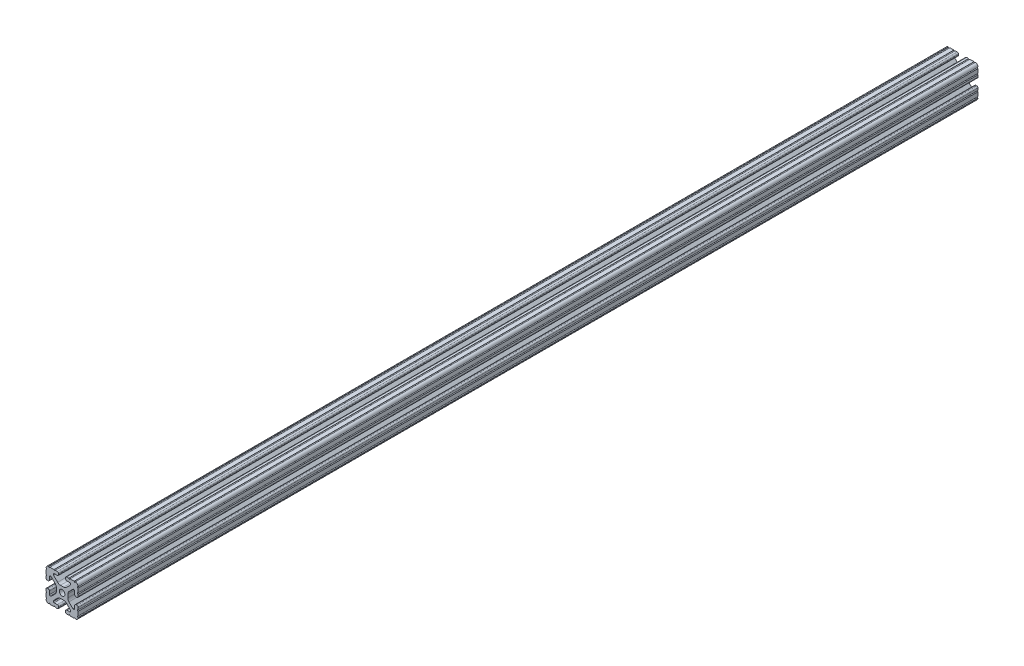
SolidWorks part; units mm, degrees
material "6061 Alloy"
ref_plane "Front Plane" through (0, 0, 0) normal (0, 0, 1) x (1, 0, 0)
ref_plane "Top Plane" through (0, 0, 0) normal (0, 1, 0) x (1, 0, 0)
ref_plane "Right Plane" through (0, 0, 0) normal (1, 0, 0) x (0, 0, -1)
sketch "Sketch1" plane through (0, 0, 0) normal (0, 0, 1) x (1, 0, 0)
  line L0 (0, 25.6181) -> (0, -24.623) construction
  line L1 (-20.8943, 0) -> (20.4607, 0) construction
  line L2 (-10.0229, 12.9148) -> (-5.2522, 8.144)
  line L3 (-10.287, 14.0843) -> (-10.287, 13.5524)
  line L4 (-5.6176, 14.986) -> (-9.3853, 14.986)
  line L5 (-4.064, 17.4964) -> (-4.064, 16.5396)
  line L6 (-7.9742, 19.05) -> (-5.6176, 19.05)
  line L7 (-14.3277, 19.05) -> (-9.4982, 19.05)
  line L8 (-19.05, 9.4961) -> (-19.05, 14.3277)
  line L9 (-19.05, 5.6176) -> (-19.05, 7.9763)
  line L10 (-16.5396, 4.064) -> (-17.4964, 4.064)
  line L11 (-14.986, 9.3853) -> (-14.986, 5.6176)
  line L12 (-13.516, 10.287) -> (-14.0843, 10.287)
  line L13 (-8.1476, 5.2921) -> (-12.8784, 10.0229)
  line L14 (-6.7564, -1.9335) -> (-6.7564, 1.9335)
  line L15 (-12.8784, -10.0229) -> (-8.1476, -5.2921)
  line L16 (-14.0843, -10.287) -> (-13.516, -10.287)
  line L17 (-14.986, -5.6176) -> (-14.986, -9.3853)
  line L18 (-17.4964, -4.064) -> (-16.5396, -4.064)
  line L19 (-19.05, -7.9763) -> (-19.05, -5.6176)
  line L20 (-19.05, -14.3277) -> (-19.05, -9.4961)
  line L21 (-9.4961, -19.05) -> (-14.3277, -19.05)
  line L22 (-5.6176, -19.05) -> (-7.9763, -19.05)
  line L23 (-4.064, -17.4964) -> (-4.064, -16.5396)
  line L24 (10.0229, -12.9148) -> (5.2522, -8.144)
  line L25 (10.287, -14.0843) -> (10.287, -13.5524)
  line L26 (5.6176, -14.986) -> (9.3853, -14.986)
  line L28 (-1.9022, 6.7564) -> (1.9022, 6.7564)
  line L29 (-1.9022, -6.7564) -> (1.9022, -6.7564)
  line L31 (-5.6176, -14.986) -> (-9.3853, -14.986)
  line L32 (-10.287, -14.0843) -> (-10.287, -13.5524)
  line L33 (-10.0229, -12.9148) -> (-5.2522, -8.144)
  line L66 (4.064, -16.5396) -> (4.064, -17.4964)
  line L67 (5.6176, -19.05) -> (7.9763, -19.05)
  line L68 (9.4961, -19.05) -> (14.3277, -19.05)
  line L69 (19.05, -14.3277) -> (19.05, -9.4961)
  line L70 (19.05, -7.9763) -> (19.05, -5.6176)
  line L71 (17.4964, -4.064) -> (16.5396, -4.064)
  line L72 (14.986, -5.6176) -> (14.986, -9.3853)
  line L73 (14.0843, -10.287) -> (13.516, -10.287)
  line L74 (12.8784, -10.0229) -> (8.1476, -5.2921)
  line L75 (6.7564, -1.9335) -> (6.7564, 1.9335)
  line L76 (8.1476, 5.2921) -> (12.8784, 10.0229)
  line L77 (13.516, 10.287) -> (14.0843, 10.287)
  line L78 (14.986, 9.3853) -> (14.986, 5.6176)
  line L79 (16.5396, 4.064) -> (17.4964, 4.064)
  line L80 (19.05, 5.6176) -> (19.05, 7.9763)
  line L81 (19.05, 9.4961) -> (19.05, 14.3277)
  line L82 (14.3277, 19.05) -> (9.4982, 19.05)
  line L83 (7.9742, 19.05) -> (5.6176, 19.05)
  line L84 (4.064, 17.4964) -> (4.064, 16.5396)
  line L85 (5.6176, 14.986) -> (9.3853, 14.986)
  line L86 (10.287, 14.0843) -> (10.287, 13.5524)
  line L87 (10.0229, 12.9148) -> (5.2522, 8.144)
  arc A0 (-10.0229, 12.9148) -> (-10.287, 13.5524) centre (-9.3853, 13.5524) cw
  circle A1 centre (0, 0) radius 3.3274
  arc A2 (-10.287, 14.0843) -> (-9.3853, 14.986) centre (-9.3853, 14.0843) cw
  arc A3 (-4.064, 16.5396) -> (-5.6176, 14.986) centre (-5.6176, 16.5396) cw
  arc A4 (-5.6176, 19.05) -> (-4.064, 17.4964) centre (-5.6176, 17.4964) cw
  arc A5 (-7.9742, 19.05) -> (-9.4982, 19.05) centre (-8.7362, 19.05) cw
  arc A6 (-14.3277, 19.05) -> (-15.8475, 19.05) centre (-15.0876, 18.9933) cw
  arc A7 (-19.05, 15.8475) -> (-15.8475, 19.05) centre (-15.8751, 15.8751) cw
  arc A8 (-19.05, 15.8475) -> (-19.05, 14.3277) centre (-18.9933, 15.0876) cw
  arc A9 (-19.05, 9.4961) -> (-19.05, 7.9763) centre (-18.9933, 8.7362) cw
  arc A10 (-17.4964, 4.064) -> (-19.05, 5.6176) centre (-17.4964, 5.6176) cw
  arc A11 (-14.986, 5.6176) -> (-16.5396, 4.064) centre (-16.5396, 5.6176) cw
  arc A12 (-14.986, 9.3853) -> (-14.0843, 10.287) centre (-14.0843, 9.3853) cw
  arc A13 (-13.516, 10.287) -> (-12.8784, 10.0229) centre (-13.516, 9.3853) cw
  arc A14 (-8.1476, 5.2921) -> (-6.7564, 1.9335) centre (-11.5062, 1.9335) cw
  arc A15 (-6.7564, -1.9335) -> (-8.1476, -5.2921) centre (-11.5062, -1.9335) cw
  arc A16 (-12.8784, -10.0229) -> (-13.516, -10.287) centre (-13.516, -9.3853) cw
  arc A17 (-14.0843, -10.287) -> (-14.986, -9.3853) centre (-14.0843, -9.3853) cw
  arc A18 (-16.5396, -4.064) -> (-14.986, -5.6176) centre (-16.5396, -5.6176) cw
  arc A19 (-19.05, -5.6176) -> (-17.4964, -4.064) centre (-17.4964, -5.6176) cw
  arc A20 (-19.05, -7.9763) -> (-19.05, -9.4961) centre (-18.9933, -8.7362) cw
  arc A21 (-19.05, -14.3277) -> (-19.05, -15.8475) centre (-18.9933, -15.0876) cw
  arc A22 (-15.8475, -19.05) -> (-19.05, -15.8475) centre (-15.8751, -15.8751) cw
  arc A23 (-15.8475, -19.05) -> (-14.3277, -19.05) centre (-15.0876, -18.9933) cw
  arc A24 (-9.4961, -19.05) -> (-7.9763, -19.05) centre (-8.7362, -18.9933) cw
  arc A25 (-4.064, -17.4964) -> (-5.6176, -19.05) centre (-5.6176, -17.4964) cw
  arc A26 (-5.2522, -8.144) -> (-1.9022, -6.7564) centre (-1.9022, -11.494) cw
  arc A27 (1.9022, -6.7564) -> (5.2522, -8.144) centre (1.9022, -11.494) cw
  arc A28 (10.0229, -12.9148) -> (10.287, -13.5524) centre (9.3853, -13.5524) cw
  arc A29 (10.287, -14.0843) -> (9.3853, -14.986) centre (9.3853, -14.0843) cw
  arc A30 (4.064, -16.5396) -> (5.6176, -14.986) centre (5.6176, -16.5396) cw
  arc A31 (-4.064, -16.5396) -> (-5.6176, -14.986) centre (-5.6176, -16.5396) ccw
  arc A32 (-10.287, -14.0843) -> (-9.3853, -14.986) centre (-9.3853, -14.0843) ccw
  arc A33 (-10.0229, -12.9148) -> (-10.287, -13.5524) centre (-9.3853, -13.5524) ccw
  arc A79 (4.064, -17.4964) -> (5.6176, -19.05) centre (5.6176, -17.4964) ccw
  arc A80 (9.4961, -19.05) -> (7.9763, -19.05) centre (8.7362, -18.9933) ccw
  arc A81 (15.8475, -19.05) -> (14.3277, -19.05) centre (15.0876, -18.9933) ccw
  arc A82 (15.8475, -19.05) -> (19.05, -15.8475) centre (15.8751, -15.8751) ccw
  arc A83 (19.05, -14.3277) -> (19.05, -15.8475) centre (18.9933, -15.0876) ccw
  arc A84 (19.05, -7.9763) -> (19.05, -9.4961) centre (18.9933, -8.7362) ccw
  arc A85 (19.05, -5.6176) -> (17.4964, -4.064) centre (17.4964, -5.6176) ccw
  arc A86 (16.5396, -4.064) -> (14.986, -5.6176) centre (16.5396, -5.6176) ccw
  arc A87 (14.0843, -10.287) -> (14.986, -9.3853) centre (14.0843, -9.3853) ccw
  arc A88 (12.8784, -10.0229) -> (13.516, -10.287) centre (13.516, -9.3853) ccw
  arc A89 (6.7564, -1.9335) -> (8.1476, -5.2921) centre (11.5062, -1.9335) ccw
  arc A90 (8.1476, 5.2921) -> (6.7564, 1.9335) centre (11.5062, 1.9335) ccw
  arc A91 (13.516, 10.287) -> (12.8784, 10.0229) centre (13.516, 9.3853) ccw
  arc A92 (14.986, 9.3853) -> (14.0843, 10.287) centre (14.0843, 9.3853) ccw
  arc A93 (14.986, 5.6176) -> (16.5396, 4.064) centre (16.5396, 5.6176) ccw
  arc A94 (17.4964, 4.064) -> (19.05, 5.6176) centre (17.4964, 5.6176) ccw
  arc A95 (19.05, 9.4961) -> (19.05, 7.9763) centre (18.9933, 8.7362) ccw
  arc A96 (19.05, 15.8475) -> (19.05, 14.3277) centre (18.9933, 15.0876) ccw
  arc A97 (19.05, 15.8475) -> (15.8475, 19.05) centre (15.8751, 15.8751) ccw
  arc A98 (14.3277, 19.05) -> (15.8475, 19.05) centre (15.0876, 18.9933) ccw
  arc A99 (7.9742, 19.05) -> (9.4982, 19.05) centre (8.7362, 19.05) ccw
  arc A100 (5.6176, 19.05) -> (4.064, 17.4964) centre (5.6176, 17.4964) ccw
  arc A101 (4.064, 16.5396) -> (5.6176, 14.986) centre (5.6176, 16.5396) ccw
  arc A102 (10.287, 14.0843) -> (9.3853, 14.986) centre (9.3853, 14.0843) ccw
  arc A103 (10.0229, 12.9148) -> (10.287, 13.5524) centre (9.3853, 13.5524) ccw
  arc A104 (1.9022, 6.7564) -> (5.2522, 8.144) centre (1.9022, 11.494) ccw
  arc A105 (-5.2522, 8.144) -> (-1.9022, 6.7564) centre (-1.9022, 11.494) ccw
  dimension "D1" = 6.6548
  dimension "D2" = 19.05
  dimension "D3" = 38.1
  dimension "D4" = 20.574
  dimension "D5" = 13.5128
  dimension "D6" = 4.064
  dimension "D7" = 8.128
  dimension "D8" = 4.064
  dimension "D9" = 12.2936
extrude "Extrude1" add sketch "Sketch1" against normal blind 1066.8
